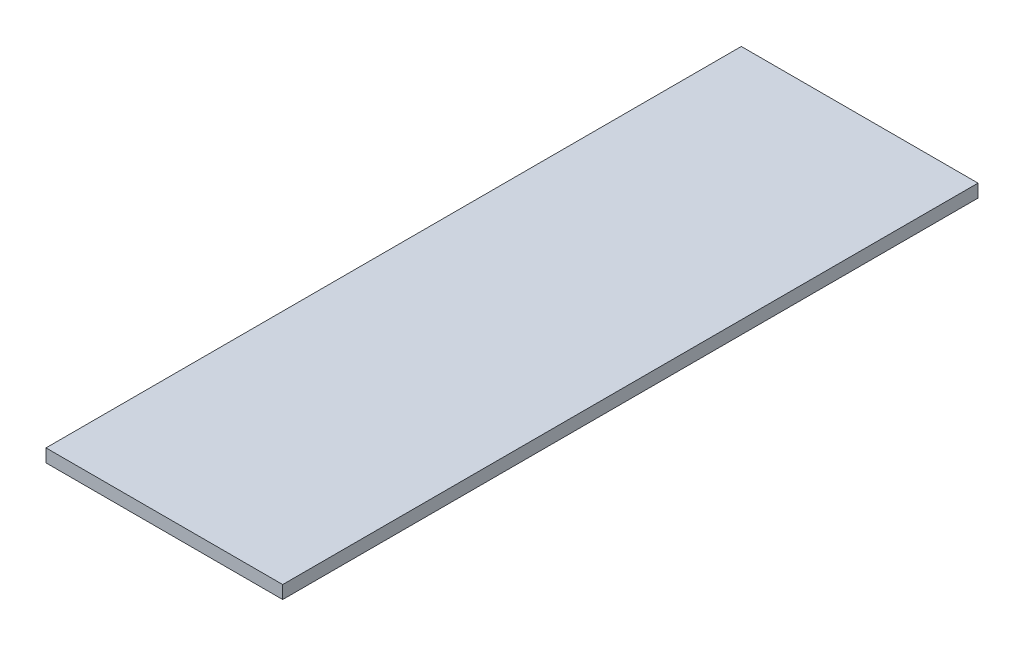
SolidWorks part; units mm, degrees
ref_plane "Front Plane" through (0, 0, 0) normal (0, 0, 1) x (1, 0, 0)
ref_plane "Top Plane" through (0, 0, 0) normal (0, 1, 0) x (1, 0, 0)
ref_plane "Right Plane" through (0, 0, 0) normal (1, 0, 0) x (0, 0, -1)
sketch "Sketch1" plane through (0, 0, 0) normal (0, 1, 0) x (1, 0, 0)
  line L0 (11.122, -9.411) -> (11.122, -19.379)
  line L1 (0, 0) -> (127.76, 0)
  line L2 (0, 0) -> (0, -85.48)
  line L3 (0, -85.48) -> (127.76, -85.48)
  line L4 (127.76, 0) -> (127.76, -85.48)
  line L5 (23.122, -9.411) -> (23.122, -19.379)
  line L6 (42.294, -9.411) -> (42.294, -19.379)
  line L7 (54.294, -9.411) -> (54.294, -19.379)
  line L8 (73.466, -9.411) -> (73.466, -19.379)
  line L9 (85.466, -9.411) -> (85.466, -19.379)
  line L10 (104.638, -9.411) -> (104.638, -19.379)
  line L11 (116.638, -9.411) -> (116.638, -19.379)
  line L12 (42.294, -37.756) -> (42.294, -47.724)
  line L13 (54.294, -37.756) -> (54.294, -47.724)
  line L14 (73.466, -37.756) -> (73.466, -47.724)
  line L15 (85.466, -37.756) -> (85.466, -47.724)
  line L16 (104.638, -37.756) -> (104.638, -47.724)
  line L17 (116.638, -37.756) -> (116.638, -47.724)
  line L18 (42.294, -66.101) -> (42.294, -76.069)
  line L19 (54.294, -66.101) -> (54.294, -76.069)
  line L20 (73.466, -66.101) -> (73.466, -76.069)
  line L21 (85.466, -66.101) -> (85.466, -76.069)
  line L22 (104.638, -66.101) -> (104.638, -76.069)
  line L23 (116.638, -66.101) -> (116.638, -76.069)
  line L24 (11.122, -37.756) -> (11.122, -47.724)
  line L25 (23.122, -37.756) -> (23.122, -47.724)
  line L26 (11.122, -66.101) -> (11.122, -76.069)
  line L27 (23.122, -66.101) -> (23.122, -76.069)
  circle A2 centre (17.122, -14.395) radius 14.05
  circle A12 centre (48.294, -14.395) radius 14.05
  circle A13 centre (79.466, -14.395) radius 14.05
  circle A14 centre (110.638, -14.395) radius 14.05
  circle A15 centre (48.294, -42.74) radius 14.05
  circle A16 centre (79.466, -42.74) radius 14.05
  circle A17 centre (110.638, -42.74) radius 14.05
  circle A18 centre (48.294, -71.085) radius 14.05
  circle A19 centre (79.466, -71.085) radius 14.05
  circle A20 centre (110.638, -71.085) radius 14.05
  circle A21 centre (17.122, -42.74) radius 14.05
  circle A22 centre (17.122, -71.085) radius 14.05
  arc A23 (11.122, -19.379) -> (23.122, -19.379) centre (17.122, -14.395) ccw
  arc A24 (23.122, -9.411) -> (11.122, -9.411) centre (17.122, -14.395) ccw
  arc A25 (42.294, -19.379) -> (54.294, -19.379) centre (48.294, -14.395) ccw
  arc A26 (54.294, -9.411) -> (42.294, -9.411) centre (48.294, -14.395) ccw
  arc A27 (73.466, -19.379) -> (85.466, -19.379) centre (79.466, -14.395) ccw
  arc A28 (85.466, -9.411) -> (73.466, -9.411) centre (79.466, -14.395) ccw
  arc A29 (104.638, -19.379) -> (116.638, -19.379) centre (110.638, -14.395) ccw
  arc A30 (116.638, -9.411) -> (104.638, -9.411) centre (110.638, -14.395) ccw
  arc A31 (42.294, -47.724) -> (54.294, -47.724) centre (48.294, -42.74) ccw
  arc A32 (54.294, -37.756) -> (42.294, -37.756) centre (48.294, -42.74) ccw
  arc A33 (73.466, -47.724) -> (85.466, -47.724) centre (79.466, -42.74) ccw
  arc A34 (85.466, -37.756) -> (73.466, -37.756) centre (79.466, -42.74) ccw
  arc A35 (104.638, -47.724) -> (116.638, -47.724) centre (110.638, -42.74) ccw
  arc A36 (116.638, -37.756) -> (104.638, -37.756) centre (110.638, -42.74) ccw
  arc A37 (42.294, -76.069) -> (54.294, -76.069) centre (48.294, -71.085) ccw
  arc A38 (54.294, -66.101) -> (42.294, -66.101) centre (48.294, -71.085) ccw
  arc A39 (73.466, -76.069) -> (85.466, -76.069) centre (79.466, -71.085) ccw
  arc A40 (85.466, -66.101) -> (73.466, -66.101) centre (79.466, -71.085) ccw
  arc A41 (104.638, -76.069) -> (116.638, -76.069) centre (110.638, -71.085) ccw
  arc A42 (116.638, -66.101) -> (104.638, -66.101) centre (110.638, -71.085) ccw
  arc A43 (11.122, -47.724) -> (23.122, -47.724) centre (17.122, -42.74) ccw
  arc A44 (23.122, -37.756) -> (11.122, -37.756) centre (17.122, -42.74) ccw
  arc A45 (11.122, -76.069) -> (23.122, -76.069) centre (17.122, -71.085) ccw
  arc A46 (23.122, -66.101) -> (11.122, -66.101) centre (17.122, -71.085) ccw
  point P15 (0, 0)
  point P34 (0, 0)
  dimension "D3" = 4
  dimension "D4" = 14.395
  dimension "D9" = 15.6
  dimension "D11" = 28.1
  dimension "D1" = 127.76
  dimension "D2" = 85.48
  dimension "D5" = 3
  dimension "D6" = 14.395
  dimension "D7" = 17.122
  dimension "D8" = 17.122
  dimension "D10" = 12
  dimension "D12" = 4
  dimension "D13" = 3
sketch "Sketch2" plane through (0, 0, 0) normal (0, 1, 0) x (1, 0, 0)
  line L0 (0, 0) -> (127.76, 0) construction
  line L1 (0, 0) -> (29.1, 0)
  line L2 (0, 0) -> (0, -85.48)
  line L3 (0, -85.48) -> (29.1, -85.48)
  line L4 (29.1, 0) -> (29.1, -85.48)
  line L5 (0, -85.48) -> (127.76, -85.48) construction
  line L6 (0, 0) -> (0, -85.48) construction
  point P8 (0, 0)
  dimension "D1" = 29.1
extrude "Boss-Extrude1" add sketch "Sketch2" along normal blind 1.6
